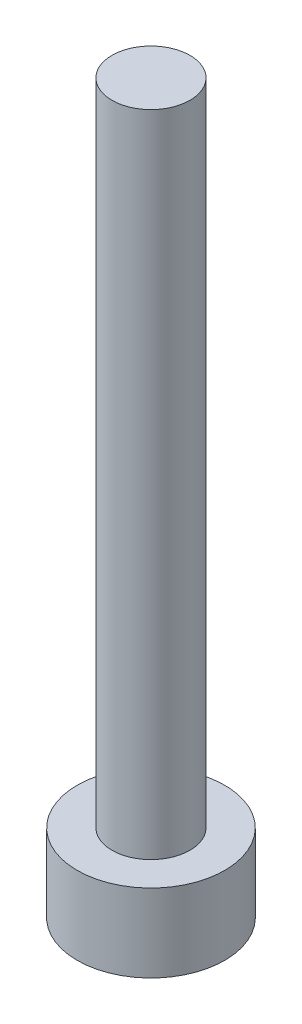
SolidWorks part; units mm, degrees
ref_plane "Front Plane" through (0, 0, 0) normal (0, 0, 1) x (1, 0, 0)
ref_plane "Top Plane" through (0, 0, 0) normal (0, 1, 0) x (1, 0, 0)
ref_plane "Right Plane" through (0, 0, 0) normal (1, 0, 0) x (0, 0, -1)
sketch "Sketch1" plane through (0, 0, 0) normal (0, 1, 0) x (1, 0, 0)
  circle A0 centre (0, 0) radius 2.84
  dimension "D1" = 5.68
extrude "Boss-Extrude1" add sketch "Sketch1" along normal blind 3
sketch "Sketch2" plane through (0, 3, 0) normal (0, 1, 0) x (1, 0, 0)
  circle A0 centre (0, 0) radius 1.5
  dimension "D1" = 3
extrude "Boss-Extrude2" add sketch "Sketch2" along normal blind 25
sketch "Sketch3" plane through (0, 0, 0) normal (0, -1, 0) x (1, 0, 0)
  line L1 (0.7448, 1.29) -> (-0.7448, 1.29)
  line L2 (-0.7448, 1.29) -> (-1.4896, 0)
  line L3 (-1.4896, 0) -> (-0.7448, -1.29)
  line L4 (-0.7448, -1.29) -> (0.7448, -1.29)
  line L5 (0.7448, -1.29) -> (1.4896, 0)
  line L6 (1.4896, 0) -> (0.7448, 1.29)
  circle A0 centre (0, 0) radius 1.29 construction
  dimension "D1" = 2.58
extrude "Cut-Extrude1" cut sketch "Sketch3" against normal blind 1.3
